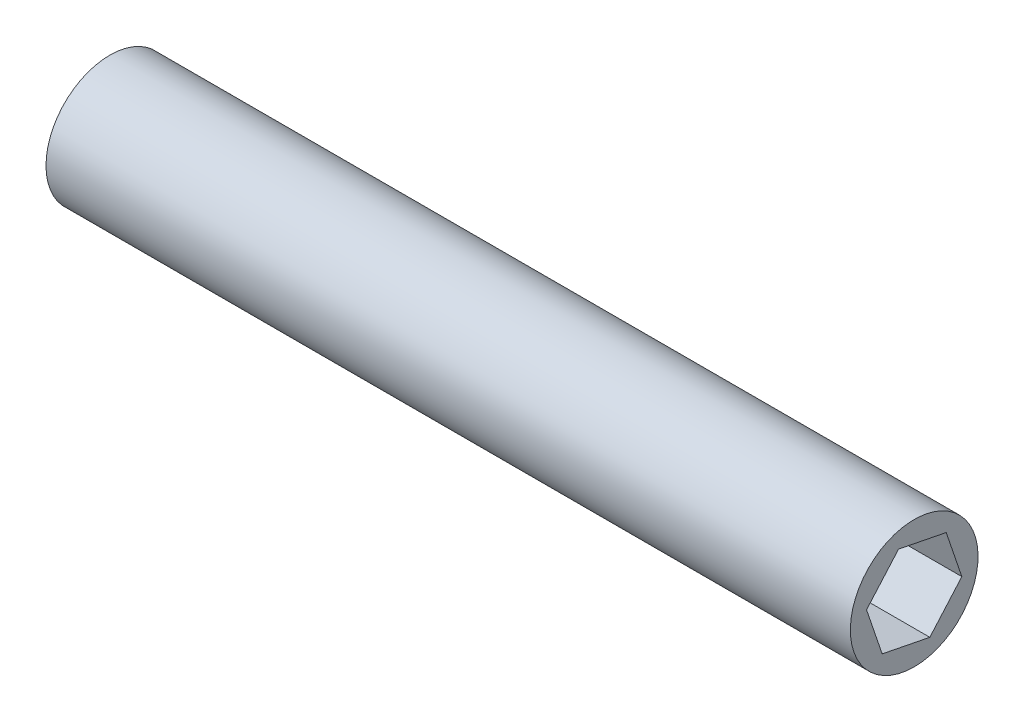
SolidWorks part; units mm, degrees
ref_plane "Front Plane" through (0, 0, 0) normal (0, 0, 1) x (1, 0, 0)
ref_plane "Top Plane" through (0, 0, 0) normal (0, 1, 0) x (1, 0, 0)
ref_plane "Right Plane" through (0, 0, 0) normal (1, 0, 0) x (0, 0, -1)
sketch "Sketch1" plane through (193.3575, 0, 0) normal (1, 0, 0) x (0, 0, -1)
  line L6 (157.9713, 188.6058) -> (153.1304, 183.0833)
  line L7 (165.1744, 187.1747) -> (157.9713, 188.6058)
  line L8 (167.5366, 180.221) -> (165.1744, 187.1747)
  line L9 (162.6957, 174.6985) -> (167.5366, 180.221)
  line L10 (155.4926, 176.1296) -> (162.6957, 174.6985)
  line L11 (153.1304, 183.0833) -> (155.4926, 176.1296)
  line L12 (157.9713, 188.6058) -> (153.1304, 183.0833)
  line L13 (165.1744, 187.1747) -> (157.9713, 188.6058)
  line L14 (167.5366, 180.221) -> (165.1744, 187.1747)
  line L15 (162.6957, 174.6985) -> (167.5366, 180.221)
  line L16 (155.4926, 176.1296) -> (162.6957, 174.6985)
  line L17 (153.1304, 183.0833) -> (155.4926, 176.1296)
  arc A2 (169.4726, 184.7567) -> (151.1944, 178.5476) centre (160.3335, 181.6522) ccw
  arc A3 (151.1944, 178.5476) -> (169.4726, 184.7567) centre (160.3335, 181.6522) ccw
  arc A4 (169.4726, 184.7567) -> (151.1944, 178.5476) centre (160.3335, 181.6522) ccw
  arc A5 (151.1944, 178.5476) -> (169.4726, 184.7567) centre (160.3335, 181.6522) ccw
  dimension "D1" = 0
  dimension "D2" = 0
extrude "Boss-Extrude1" add sketch "Sketch1" along normal up to surface (121.6025 mm away)
